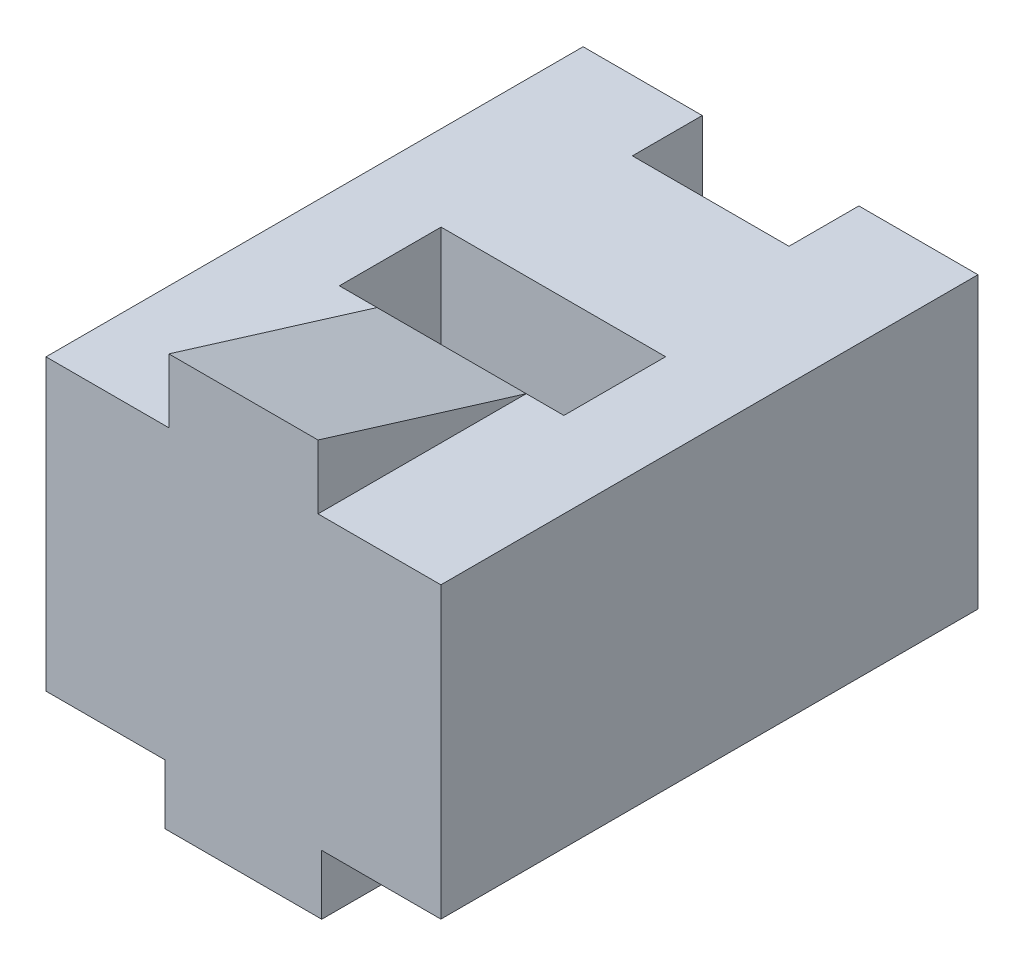
SolidWorks part; units mm, degrees
ref_plane "Спереди" through (0, 0, 0) normal (0, 0, 1) x (1, 0, 0)
ref_plane "Сверху" through (0, 0, 0) normal (0, 1, 0) x (1, 0, 0)
ref_plane "Справа" through (0, 0, 0) normal (1, 0, 0) x (0, 0, -1)
sketch "Эскиз1" plane through (0, 0, 0) normal (0, 0, 1) x (1, 0, 0)
  line L1 (-66.1685, 0) -> (66.1685, 0)
  line L2 (-66.1685, 0) -> (-66.1685, -97.0341)
  line L3 (-66.1685, -97.0341) -> (66.1685, -97.0341)
  line L4 (66.1685, 0) -> (66.1685, -97.0341)
  point P4 (0, 0)
other "Перо1" parameters "D1"=97.0341, "D2"=149.5063
extrude "Бобышка-Вытянуть1" add sketch "Эскиз1" along normal blind 180
sketch "Эскиз2" plane through (0, 0, 0) normal (0, 1, 0) x (1, 0, 0)
  line L0 (0, 0) -> (0, -180) construction
  line L1 (66.1685, 0) -> (-66.1685, 0) construction
  line L2 (66.1685, -180) -> (-66.1685, -180) construction
  line L3 (-26.2409, 0) -> (-26.2409, -23.4169)
  line L4 (-26.2409, -23.4169) -> (26.2409, -23.4169)
  line L5 (26.2409, -23.4169) -> (26.2409, 0)
  line L7 (-37.625, -76.1438) -> (37.625, -76.1438)
  line L8 (-37.625, -76.1438) -> (-37.625, -110.2324)
  line L9 (-37.625, -110.2324) -> (37.625, -110.2324)
  line L10 (37.625, -76.1438) -> (37.625, -110.2324)
  point P8 (-30.41, -23.1716)
  point P11 (0, 0)
  point P16 (-26.2409, -23.4169)
  line M4 (66.1685, 0) -> (-66.1685, 0)
other "Перо2" parameters "D1"=9.8453, "D2"=75.2501
sketch "Эскиз3" plane through (0, 0, 0) normal (0, 1, 0) x (1, 0, 0)
other "Перо3"
extrude "Вырез-Вытянуть2" cut sketch "Эскиз2" against normal through all contours L0 L7 L8 L9 | L7 L0 L9 L10 | L0 L4 L5 M4 | L0 L3 L4 M4
sketch "Эскиз6" plane through (0, -97.0341, 0) normal (0, -1, 0) x (-1, 0, 0)
  line L0 (26.2409, -180) -> (26.2409, -157.3189)
  line L1 (66.1685, -180) -> (-66.1685, -180) construction
  line L2 (26.2409, -157.3189) -> (-26.2409, -157.3189)
  line L3 (-26.2409, -157.3189) -> (-26.2409, -180)
  line L4 (0, -23.4169) -> (0, -180) construction
  line L5 (26.2409, -23.4169) -> (-26.2409, -23.4169) construction
  line L12 (26.2409, 0) -> (26.2409, -23.4169) construction
  line L13 (-66.1685, -180) -> (-26.2409, -180)
  line L14 (26.2409, -180) -> (-26.2409, -180)
  line L15 (26.2409, -180) -> (-26.2409, -180)
  line L21 (26.2409, -23.4169) -> (-26.2409, -23.4169)
  line L22 (-26.2409, -23.4169) -> (-26.2409, 0)
  line L23 (-26.2409, 0) -> (-66.1685, 0)
  line L24 (-66.1685, 0) -> (-66.1685, -180)
  line L25 (-66.1685, -180) -> (66.1685, -180)
  line L26 (66.1685, -180) -> (66.1685, 0)
  line L27 (66.1685, 0) -> (26.2409, 0)
  line L28 (26.2409, 0) -> (26.2409, -23.4169)
  line L29 (26.2409, -23.4169) -> (-26.2409, -23.4169)
  line L30 (-26.2409, -23.4169) -> (-26.2409, 0)
  line L31 (-26.2409, 0) -> (-66.1685, 0)
  line L32 (-66.1685, 0) -> (-66.1685, -180)
  line L33 (26.2409, -180) -> (66.1685, -180)
  line L34 (66.1685, -180) -> (66.1685, 0)
  line L35 (66.1685, 0) -> (26.2409, 0)
  line L36 (26.2409, 0) -> (26.2409, -23.4169)
  line M12 (-66.1685, -180) -> (66.1685, -180)
other "Перо4" parameters "D1"=7.75, "D2"=52.4817
extrude "Бобышка-Вытянуть2" add sketch "Эскиз6" along normal blind 20 contours L2 L4 L15 L0 | L4 L2 L3 M12
sketch "Эскиз8" plane through (0, 0, 0) normal (1, 0, 0) x (0, 0, -1)
  line L0 (-180, 0) -> (-180, 21.4428)
  line L1 (-180, 21.4428) -> (-110.2324, 0)
  line L2 (-110.2324, 0) -> (-180, 0)
  line L3 (-110.2324, -97.0341) -> (-110.2324, 0) construction
  point P2 (-179.0723, 21.213)
  point P4 (0, 0)
  point P6 (0, 0)
extrude "Бобышка-Вытянуть3" add sketch "Эскиз8" along normal blind 25 and the other way blind 25
